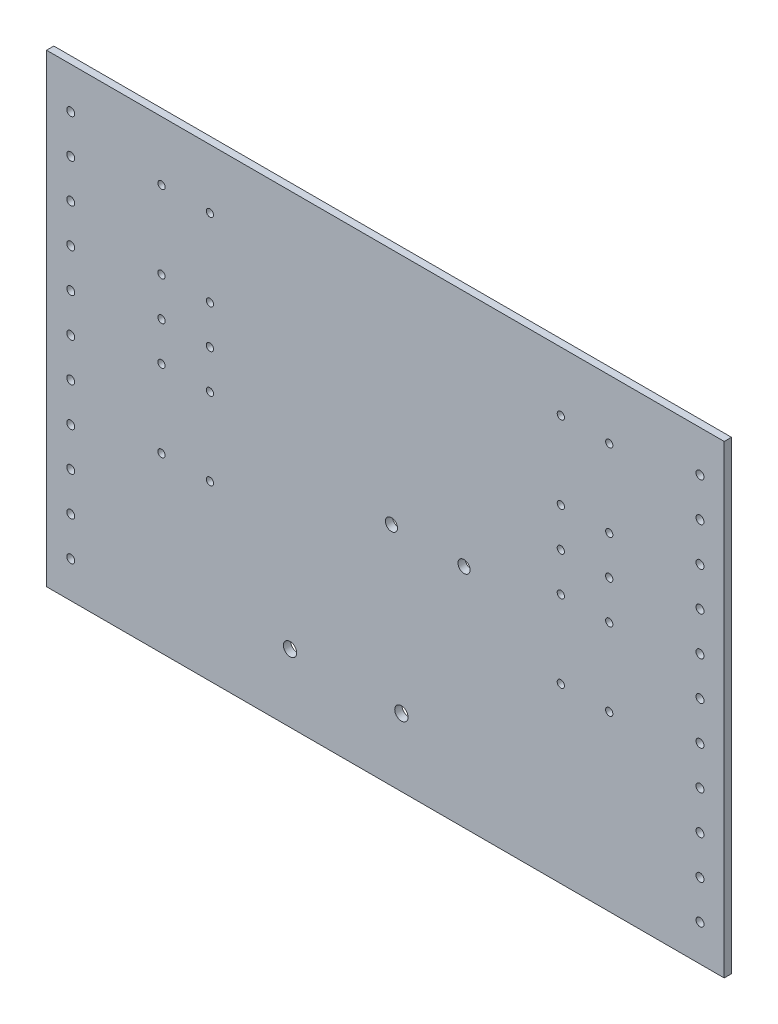
SolidWorks part; units mm, degrees
ref_plane "前视基准面" through (0, 0, 0) normal (0, 0, 1) x (1, 0, 0)
ref_plane "上视基准面" through (0, 0, 0) normal (0, 1, 0) x (1, 0, 0)
ref_plane "右视基准面" through (0, 0, 0) normal (1, 0, 0) x (0, 0, -1)
other "Configuration Table"
sketch "草图1" plane through (0, 0, 0) normal (0, 0, 1) x (1, 0, 0)
  line L1 (-140, -100) -> (140, -100)
  line L2 (-140, -100) -> (-140, 100)
  line L3 (-140, 100) -> (140, 100)
  line L4 (140, -100) -> (140, 100)
  line L5 (-140, -100) -> (140, 100) construction
  line L6 (-140, 100) -> (140, -100) construction
  point P0 (0, 0)
  dimension "D1" = 280
  dimension "D2" = 200
extrude "凸台-拉伸1" add sketch "草图1" along normal blind 3
sketch "草图2" plane through (0, 0, 0) normal (0, 0, -1) x (-1, 0, 0)
  line L0 (-140, 92) -> (140, 92) construction
  line L1 (-140, -100) -> (-140, 100) construction
  line L2 (140, 100) -> (140, -100) construction
  line L3 (-140, 100) -> (140, 100) construction
  line L4 (92.5, 100) -> (92.5, -100) construction
  line L5 (140, -100) -> (-140, -100) construction
  line L6 (82.5, 100) -> (82.5, -100) construction
  line L7 (0, 100) -> (0, -100) construction
  line L8 (-140, -72) -> (140, -72) construction
  line L9 (-140, -6.5) -> (140, -6.5) construction
  line L10 (7.5, 100) -> (7.5, -100) construction
  circle A0 centre (92.5, 19.5) radius 1.5
  circle A1 centre (92.5, 35.5) radius 1.5
  circle A2 centre (92.5, 3.5) radius 1.5
  circle A3 centre (92.5, -28.5) radius 1.5
  circle A4 centre (92.5, 67.5) radius 1.5
  circle A5 centre (72.5, 67.5) radius 1.5
  circle A6 centre (72.5, 35.5) radius 1.5
  circle A7 centre (72.5, 19.5) radius 1.5
  circle A8 centre (72.5, 3.5) radius 1.5
  circle A9 centre (72.5, -28.5) radius 1.5
  circle A10 centre (-92.5, -28.5) radius 1.5
  circle A11 centre (-92.5, 3.5) radius 1.5
  circle A12 centre (-92.5, 19.5) radius 1.5
  circle A13 centre (-92.5, 35.5) radius 1.5
  circle A14 centre (-92.5, 67.5) radius 1.5
  circle A15 centre (-72.5, -28.5) radius 1.5
  circle A16 centre (-72.5, 3.5) radius 1.5
  circle A17 centre (-72.5, 19.5) radius 1.5
  circle A18 centre (-72.5, 35.5) radius 1.5
  circle A19 centre (-72.5, 67.5) radius 1.5
  circle A20 centre (39.38, -72) radius 2.75
  circle A21 centre (-6.62, -72) radius 2.75
  circle A22 centre (-2.5, -6.5) radius 2.5
  circle A23 centre (-32.5, -6.5) radius 2.5
  dimension "D4" = 3
  dimension "D5" = 16
  dimension "D6" = 16
  dimension "D7" = 32
  dimension "D8" = 32
  dimension "D12" = 5.5
  dimension "D13" = 46
  dimension "D16" = 30
  dimension "D17" = 10
  dimension "D18" = 5
  dimension "D1" = 8
  dimension "D2" = 47.5
  dimension "D3" = 72.5
  dimension "D9" = 10
  dimension "D10" = 28
  dimension "D11" = 100.62
  dimension "D14" = 93.5
  dimension "D15" = 132.5
extrude "切除-拉伸1" cut sketch "草图2" against normal up to surface (3 mm away) up to face at (0, 0, 3)
sketch "草图3" plane through (0, 0, 0) normal (0, 0, -1) x (-1, 0, 0)
  line L0 (-140, 100) -> (-140, 92)
  line L1 (-140, -100) -> (-140, 100) construction
  line L2 (-140, 92) -> (140, 92)
  line L3 (140, 100) -> (140, -100) construction
  line L4 (140, 92) -> (140, 100)
  line L5 (140, 100) -> (-140, 100)
  dimension "D1" = 8
extrude "切除-拉伸2" cut sketch "草图3" against normal through all
sketch "草图4" plane through (0, 0, 0) normal (0, 0, -1) x (-1, 0, 0)
  line L0 (0, 0) -> (0, 92) construction
  line L1 (-140, 92) -> (140, 92) construction
  line L3 (-140, -100) -> (-140, 92) construction
  circle A36 centre (-130, 75) radius 1.65
  circle A37 centre (-130, 59) radius 1.65
  circle A38 centre (-130, 43) radius 1.65
  circle A39 centre (-130, 27) radius 1.65
  circle A40 centre (-130, 11) radius 1.65
  circle A41 centre (-130, -5) radius 1.65
  circle A42 centre (-130, -21) radius 1.65
  circle A43 centre (-130, -37) radius 1.65
  circle A44 centre (-130, -53) radius 1.65
  circle A45 centre (-130, -69) radius 1.65
  circle A46 centre (-130, -85) radius 1.65
  circle A49 centre (130, -85) radius 1.65
  circle A50 centre (130, -69) radius 1.65
  circle A51 centre (130, -53) radius 1.65
  circle A52 centre (130, -37) radius 1.65
  circle A53 centre (130, -21) radius 1.65
  circle A54 centre (130, -5) radius 1.65
  circle A55 centre (130, 11) radius 1.65
  circle A56 centre (130, 27) radius 1.65
  circle A57 centre (130, 43) radius 1.65
  circle A58 centre (130, 59) radius 1.65
  circle A59 centre (130, 75) radius 1.65
  dimension "D2" = 10
  dimension "D1" = 17
extrude "切除-拉伸4" cut sketch "草图4" against normal through all
